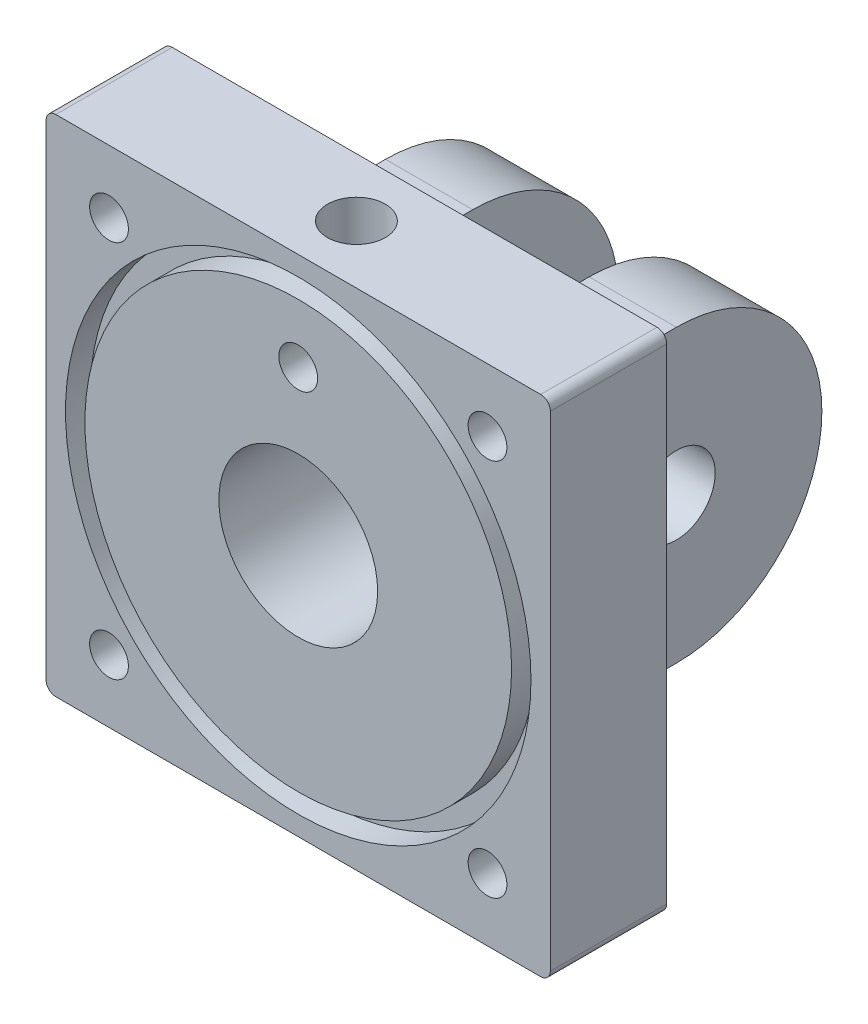
SolidWorks part; units mm, degrees
ref_plane "Front Plane" through (0, 0, 0) normal (0, 0, 1) x (1, 0, 0)
ref_plane "Top Plane" through (0, 0, 0) normal (0, 1, 0) x (1, 0, 0)
ref_plane "Right Plane" through (0, 0, 0) normal (1, 0, 0) x (0, 0, -1)
sketch "Sketch1" plane through (0, 0, 0) normal (0, 0, 1) x (1, 0, 0)
  line L1 (82.55, -82.55) -> (-82.55, -82.55)
  line L2 (82.55, -82.55) -> (82.55, 82.55)
  line L3 (82.55, 82.55) -> (-82.55, 82.55)
  line L4 (-82.55, -82.55) -> (-82.55, 82.55)
  line L5 (82.55, -82.55) -> (-82.55, 82.55) construction
  line L6 (82.55, 82.55) -> (-82.55, -82.55) construction
  point P0 (0, 0)
  dimension "D1" = 165.1
  dimension "D2" = 165.1
extrude "Boss-Extrude1" add sketch "Sketch1" along normal blind 38.1
sketch "Sketch2" plane through (0, 0, 0) normal (0, 0, -1) x (-1, 0, 0)
  line L0 (-82.55, 82.55) -> (82.55, 82.55) construction
  line L2 (47.625, -47.625) -> (-47.625, -47.625)
  line L3 (47.625, -47.625) -> (47.625, 47.625)
  line L4 (47.625, 47.625) -> (-47.625, 47.625)
  line L5 (-47.625, -47.625) -> (-47.625, 47.625)
  line L6 (47.625, -47.625) -> (-47.625, 47.625) construction
  line L7 (47.625, 47.625) -> (-47.625, -47.625) construction
  circle A0 centre (0, 0) radius 87.63 construction
  circle A1 centre (-73.5587, 47.625) radius 6.4456
  dimension "D1" = 175.26
  dimension "D2" = 34.925
  dimension "D3" = 95.25
extrude "Boss-Extrude2" add sketch "Sketch2" along normal blind 38.1 contours L5 L2 L3 L4
sketch "Sketch3" plane through (47.625, 0, 0) normal (1, 0, 0) x (0, 0, -1)
  line L0 (38.1, -47.625) -> (38.1, 47.625) construction
  line L1 (38.1, -47.625) -> (0, -47.625) construction
  line L2 (38.1, -47.625) -> (38.1, 47.625)
  arc A0 (38.1, 47.625) -> (38.1, -47.625) centre (38.1, 0) cw
extrude "Boss-Extrude3" add sketch "Sketch3" against normal up to surface (95.25 mm away) up to face at (-47.625, 0, -19.05)
sketch "Sketch4" plane through (47.625, 0, 0) normal (1, 0, 0) x (0, 0, -1)
  circle A0 centre (38.1, 0) radius 12.7
  dimension "D1" = 25.4
extrude "Cut-Extrude1" cut sketch "Sketch4" against normal through all
sketch "Sketch5" plane through (0, 47.625, 0) normal (0, 1, 0) x (1, 0, 0)
  line L0 (-47.625, 0) -> (47.625, 0) construction
  line L1 (-19.05, 0) -> (19.05, 0)
  line L2 (-19.05, 0) -> (-19.05, 85.725)
  line L3 (-19.05, 85.725) -> (19.05, 85.725)
  line L4 (19.05, 0) -> (19.05, 85.725)
  line L5 (47.625, 85.725) -> (-47.625, 85.725) construction
  line L6 (-47.625, 85.725) -> (-47.625, 38.1) construction
  dimension "D1" = 38.1
  dimension "D2" = 28.575
extrude "Cut-Extrude2" cut sketch "Sketch5" against normal through all
fillet "Fillet1" radius 3.175 4 edges at (82.55, 82.55, 19.05) (-82.55, -82.55, 19.05) (82.55, -82.55, 19.05) (-82.55, 82.55, 19.05)
sketch "Sketch6" plane through (0, 0, 38.1) normal (0, 0, 1) x (1, 0, 0)
  circle A0 centre (0, 0) radius 26
  dimension "D1" = 52
extrude "Cut-Extrude3" cut sketch "Sketch6" against normal blind 36.83
sketch "Sketch7" plane through (0, 0, 38.1) normal (0, 0, 1) x (1, 0, 0)
  circle A0 centre (0, 0) radius 76.2
  circle A1 centre (0, 0) radius 69.85
  dimension "D1" = 152.4
  dimension "D2" = 139.7
extrude "Cut-Extrude4" cut sketch "Sketch7" against normal blind 8
sketch "Sketch8" plane through (0, 82.55, 0) normal (0, 1, 0) x (1, 0, 0)
  line L0 (-79.375, -19.05) -> (79.375, -19.05) construction
  line L1 (-79.375, 0) -> (-79.375, -38.1) construction
  line L2 (79.375, -38.1) -> (79.375, 0) construction
hole_wizard "1/2-14 NPSM Tapped Hole1" positions "Sketch9" profile "Sketch10" tap size "1/2-14 NPSM" standard "ANSI Inch"
sketch "Sketch9" plane through (0, 82.55, 0) normal (0, 1, 0) x (1, 0, 0)
  line L0 (-79.375, -19.05) -> (79.375, -19.05) construction
  point P0 (0, -19.05)
sketch "Sketch10" plane through (0, 82.55, 19.05) normal (1, 0, 0) x (0, 0, 1)
  line L0 (0, 0) -> (0, 52.9503)
  line L1 (0, 52.9503) -> (9.4869, 47.25)
  line L2 (9.4869, 47.25) -> (9.4869, 0)
  line L5 (9.4869, 0) -> (0, 0)
  line L10 (0, 52.9503) -> (-9.4869, 47.25) construction
  line L11 (0, -6.35) -> (0, 107.95) construction
  dimension "Tap Drill Dia." = 18.9738
  dimension "Tap Drill Depth" = 47.25
  dimension "Drill Angle" = 118
cosmetic thread "Hole Thread1" parameters "D1"=41.81, "D2"=20.9042
sketch "Sketch11" plane through (0, 0, 38.1) normal (0, 0, 1) x (1, 0, 0)
  line L0 (-79.375, 82.55) -> (79.375, 82.55) construction
  circle A0 centre (0, 50.55) radius 6.35
  dimension "D1" = 12.7
  dimension "D2" = 32
extrude "Cut-Extrude5" cut sketch "Sketch11" against normal blind 20
sketch "Sketch12" plane through (0, 0, 38.1) normal (0, 0, 1) x (1, 0, 0)
  line L1 (61.9638, -61.9638) -> (-61.9638, -61.9638) construction
  line L2 (61.9638, -61.9638) -> (61.9638, 61.9638) construction
  line L3 (61.9638, 61.9638) -> (-61.9638, 61.9638) construction
  line L4 (-61.9638, -61.9638) -> (-61.9638, 61.9638) construction
  line L5 (61.9638, -61.9638) -> (-61.9638, 61.9638) construction
  line L6 (61.9638, 61.9638) -> (-61.9638, -61.9638) construction
  circle A0 centre (0, 0) radius 87.63 construction
  circle A1 centre (-61.9638, 61.9638) radius 6.35
  circle A2 centre (61.9638, 61.9638) radius 6.35
  circle A3 centre (61.9638, -61.9638) radius 6.35
  circle A4 centre (-61.9638, -61.9638) radius 6.35
  dimension "D1" = 175.26
  dimension "D2" = 12.7
  dimension "D3" = 4
extrude "Cut-Extrude6" cut sketch "Sketch12" against normal through all
